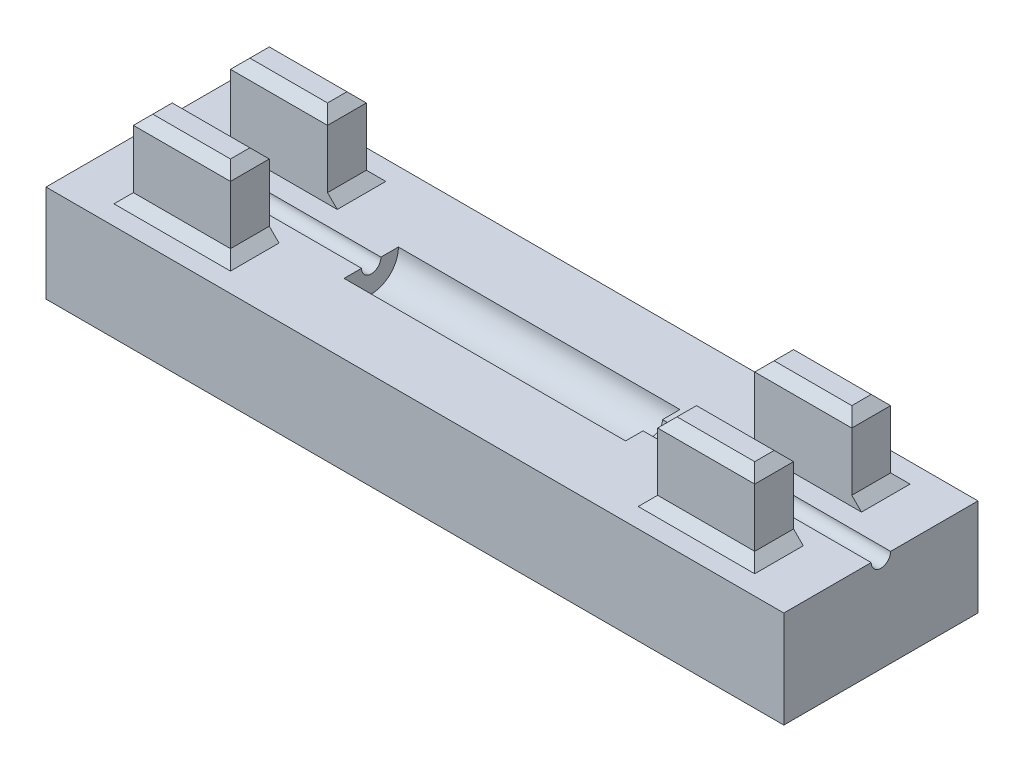
SolidWorks part; units mm, degrees
ref_plane "Front Plane" through (0, 0, 0) normal (0, 0, 1) x (1, 0, 0)
ref_plane "Top Plane" through (0, 0, 0) normal (0, 1, 0) x (1, 0, 0)
ref_plane "Right Plane" through (0, 0, 0) normal (1, 0, 0) x (0, 0, -1)
sketch "Sketch1" plane through (0, 0, 0) normal (0, 1, 0) x (1, 0, 0)
  line L1 (0, 0) -> (38, 0)
  line L2 (0, 0) -> (0, 10)
  line L3 (0, 10) -> (38, 10)
  line L4 (38, 0) -> (38, 10)
  dimension "D1" = 38
  dimension "D2" = 10
extrude "Boss-Extrude1" add sketch "Sketch1" along normal blind 5
sketch "Sketch2" plane through (0, 5, 0) normal (0, 1, 0) x (1, 0, 0)
  line L0 (0, 5) -> (38, 5)
  line L1 (0, 10) -> (0, 0) construction
  line L2 (38, 0) -> (38, 10) construction
  line L3 (38, 5) -> (38, 4.5)
  line L4 (38, 4.5) -> (26.25, 4.5)
  line L5 (26.25, 4.5) -> (26.25, 3.6)
  line L6 (26.25, 3.6) -> (11.75, 3.6)
  line L7 (11.75, 3.6) -> (11.75, 4.5)
  line L8 (11.75, 4.5) -> (0, 4.5)
  line L9 (0, 4.5) -> (0, 5)
  line L10 (19, 10) -> (19, 0) construction
  line L11 (38, 10) -> (0, 10) construction
  line L12 (0, 0) -> (38, 0) construction
  dimension "D1" = 0.5
  dimension "D2" = 1.4
  dimension "D3" = 14.5
revolve "Cut-Revolve1" cut sketch "Sketch2" angle 360 about L0
sketch "Sketch3" plane through (0, 5, 0) normal (0, 1, 0) x (1, 0, 0)
  line L0 (38, 10) -> (0, 10) construction
  line L1 (3, 8.5) -> (8, 8.5)
  line L2 (3, 8.5) -> (3, 6.5)
  line L3 (3, 6.5) -> (8, 6.5)
  line L4 (8, 8.5) -> (8, 6.5)
  line L5 (30, 8.5) -> (35, 8.5)
  line L6 (30, 8.5) -> (30, 6.5)
  line L7 (30, 6.5) -> (35, 6.5)
  line L8 (35, 8.5) -> (35, 6.5)
  line L9 (30, 3.501) -> (35, 3.501)
  line L10 (30, 3.501) -> (30, 1.501)
  line L11 (30, 1.501) -> (35, 1.501)
  line L12 (35, 3.501) -> (35, 1.501)
  line L13 (3, 3.501) -> (8, 3.501)
  line L14 (3, 3.501) -> (3, 1.501)
  line L15 (3, 1.501) -> (8, 1.501)
  line L16 (8, 3.501) -> (8, 1.501)
  line L17 (0, 0) -> (38, 0) construction
  line L18 (0, 10) -> (0, 5.5) construction
  line L19 (38, 5.5) -> (38, 10) construction
  dimension "D1" = 5
  dimension "D2" = 2
  dimension "D3" = 1.5
  dimension "D4" = 1.501
  dimension "D5" = 3
  dimension "D6" = 3
extrude "Boss-Extrude2" add sketch "Sketch3" along normal blind 4
chamfer "Chamfer1" distance 0.5 angle 45 12 edges at (30, 5, -2.501) (32.5, 5, -1.501) (35, 5, -2.501) (30, 5, -7.5) (32.5, 5, -8.5) (35, 5, -7.5) (8, 5, -7.5) (5.5, 5, -8.5) (3, 5, -7.5) (3, 5, -2.501) (5.5, 5, -1.501) (8, 5, -2.501)
chamfer "Chamfer2" distance 0.5 angle 45 16 edges at (35, 9, -7.5) (32.5, 9, -6.5) (32.5, 9, -8.5) (30, 9, -7.5) (35, 9, -2.501) (32.5, 9, -1.501) (30, 9, -2.501) (32.5, 9, -3.501) (8, 9, -7.5) (5.5, 9, -8.5) (3, 9, -7.5) (5.5, 9, -6.5) (3, 9, -2.501) (5.5, 9, -3.501) (8, 9, -2.501) (5.5, 9, -1.501)
